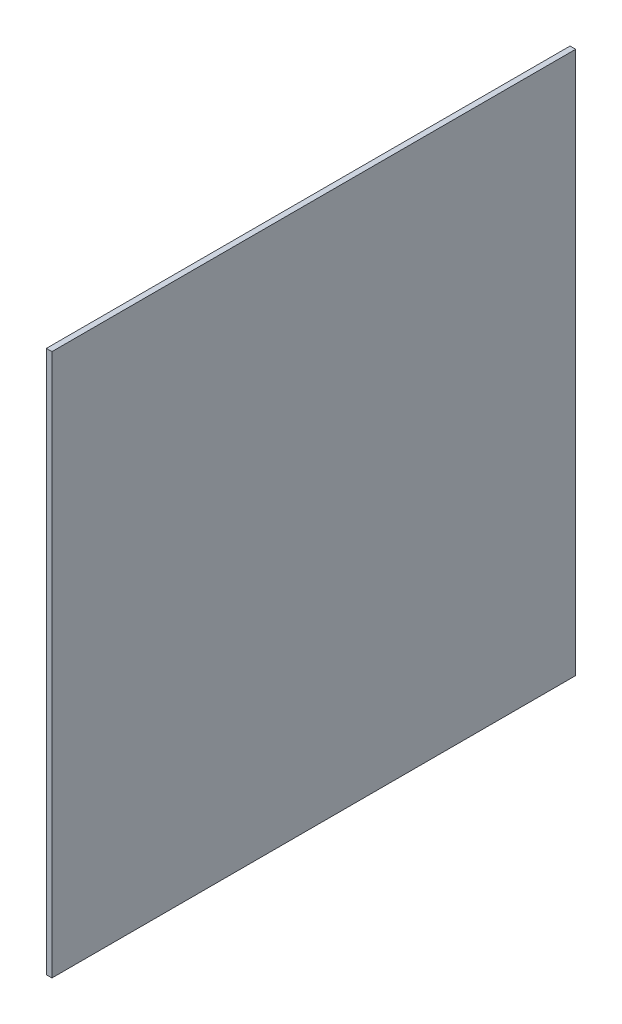
SolidWorks part; units mm, degrees
ref_plane "前视基准面" through (0, 0, 0) normal (0, 0, 1) x (1, 0, 0)
ref_plane "上视基准面" through (0, 0, 0) normal (0, 1, 0) x (1, 0, 0)
ref_plane "右视基准面" through (0, 0, 0) normal (1, 0, 0) x (0, 0, -1)
other "Configuration Table"
sketch "草图1" plane through (0, 0, 0) normal (1, 0, 0) x (0, 0, -1)
  line L1 (-46.7551, 37.9625) -> (233.2449, 37.9625)
  line L2 (-46.7551, 37.9625) -> (-46.7551, -252.0375)
  line L3 (-46.7551, -252.0375) -> (233.2449, -252.0375)
  line L4 (233.2449, 37.9625) -> (233.2449, -252.0375)
  dimension "D1" = 290
  dimension "D2" = 280
extrude "凸台-拉伸1" add sketch "草图1" along normal blind 3
